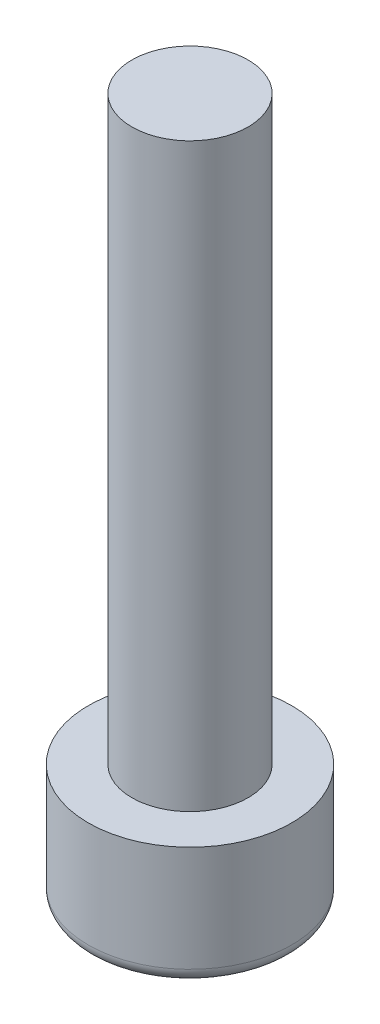
SolidWorks part; units mm, degrees
ref_plane "前视基准面" through (0, 0, 0) normal (0, 0, 1) x (1, 0, 0)
ref_plane "上视基准面" through (0, 0, 0) normal (0, 1, 0) x (1, 0, 0)
ref_plane "右视基准面" through (0, 0, 0) normal (1, 0, 0) x (0, 0, -1)
sketch "草图1" plane through (0, 0, 0) normal (0, 1, 0) x (1, 0, 0)
  circle A0 centre (0, 0) radius 3.5
  dimension "D1" = 7
extrude "凸台-拉伸1" add sketch "草图1" along normal blind 4.14
sketch "草图2" plane through (0, 4.14, 0) normal (0, 1, 0) x (1, 0, 0)
  circle A0 centre (0, 0) radius 2
  dimension "D1" = 4
extrude "凸台-拉伸2" add sketch "草图2" along normal blind 20
cosmetic thread "装饰螺纹线1" parameters "D2"=3.242
fillet "圆角1" radius 0.5 1 edges at (0, 0, 3.5)
sketch "草图3" plane through (0, 0, 0) normal (0, -1, 0) x (1, 0, 0)
  line L1 (1.6983, 2.0561) -> (-0.9315, 2.4988)
  line L2 (-0.9315, 2.4988) -> (-2.6298, 0.4427)
  line L3 (-2.6298, 0.4427) -> (-1.6983, -2.0561)
  line L4 (-1.6983, -2.0561) -> (0.9315, -2.4988)
  line L5 (0.9315, -2.4988) -> (2.6298, -0.4427)
  line L6 (2.6298, -0.4427) -> (1.6983, 2.0561)
  circle A0 centre (0, 0) radius 2.3095 construction
extrude "切除-拉伸1" cut sketch "草图3" against normal blind 2
